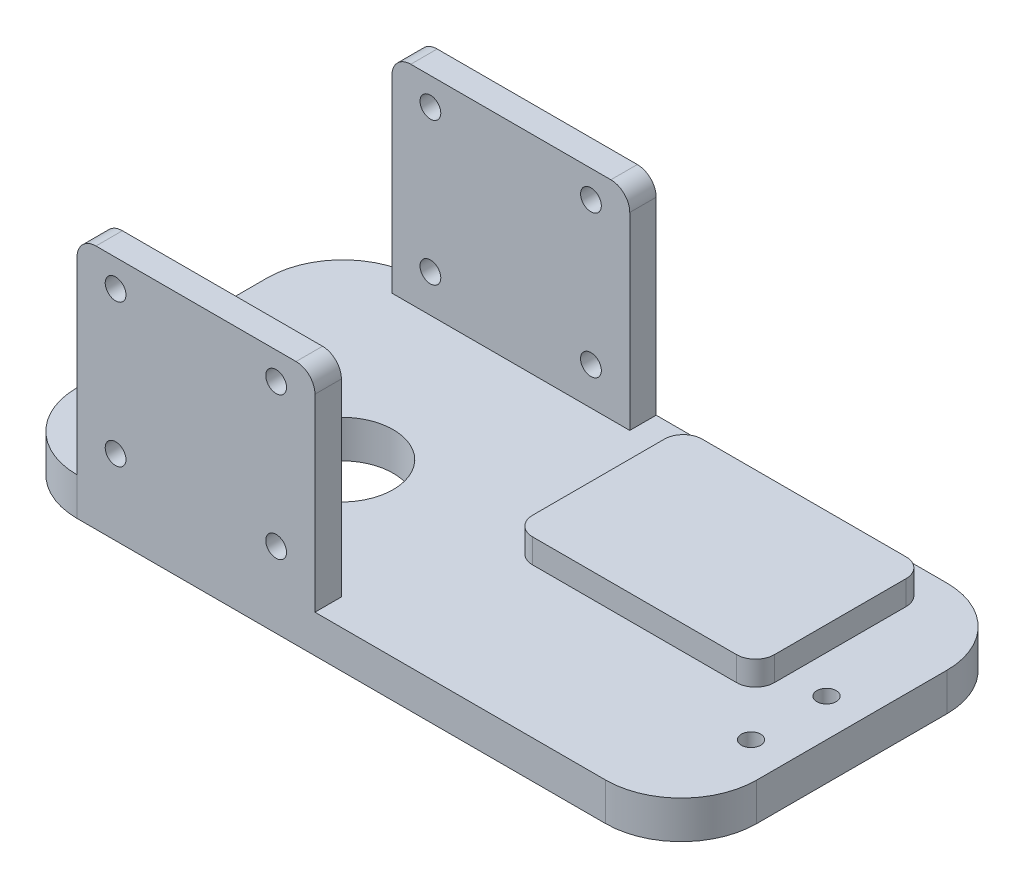
SolidWorks part; units mm, degrees
ref_plane "Front Plane" through (0, 0, 0) normal (0, 0, 1) x (1, 0, 0)
ref_plane "Top Plane" through (0, 0, 0) normal (0, 1, 0) x (1, 0, 0)
ref_plane "Right Plane" through (0, 0, 0) normal (1, 0, 0) x (0, 0, -1)
sketch "Sketch1" plane through (0, 0, 0) normal (0, 1, 0) x (1, 0, 0)
  line L1 (-114.3, -57.39) -> (114.3, -57.39)
  line L2 (-114.3, -57.39) -> (-114.3, 57.39)
  line L3 (-114.3, 57.39) -> (114.3, 57.39)
  line L4 (114.3, -57.39) -> (114.3, 57.39)
  line L5 (-114.3, -57.39) -> (114.3, 57.39) construction
  line L6 (-114.3, 57.39) -> (114.3, -57.39) construction
  point P0 (0, 0)
  dimension "D1" = 114.78
  dimension "D2" = 228.6
extrude "Boss-Extrude1" add sketch "Sketch1" along normal blind 12.7
sketch "Sketch2" plane through (0, 12.7, 0) normal (0, 1, 0) x (1, 0, 0)
  line L1 (-88.9, 57.39) -> (-8.89, 57.39)
  line L2 (-88.9, 57.39) -> (-88.9, 48.5)
  line L3 (-88.9, 48.5) -> (-8.89, 48.5)
  line L4 (-8.89, 57.39) -> (-8.89, 48.5)
  line L5 (-114.3, -57.39) -> (114.3, -57.39) construction
  line L6 (-88.9, -57.39) -> (-8.89, -57.39)
  line L7 (-88.9, -57.39) -> (-88.9, -48.5)
  line L8 (-88.9, -48.5) -> (-8.89, -48.5)
  line L9 (-8.89, -57.39) -> (-8.89, -48.5)
  line L10 (114.3, 57.39) -> (-114.3, 57.39) construction
  line L11 (-114.3, 57.39) -> (-114.3, -57.39) construction
  dimension "D1" = 8.89
  dimension "D2" = 80.01
  dimension "D3" = 25.4
extrude "Boss-Extrude2" add sketch "Sketch2" along normal blind 69.85
sketch "Sketch3" plane through (0, 12.7, 0) normal (0, 1, 0) x (1, 0, 0)
  line L0 (-88.9, 57.39) -> (-88.9, 48.5) construction
  line L1 (88.9, 50) -> (7.62, 50)
  line L2 (88.9, 50) -> (88.9, -7)
  line L3 (88.9, -7) -> (7.62, -7)
  line L4 (7.62, 50) -> (7.62, -7)
  line L5 (114.3, -57.39) -> (114.3, 57.39) construction
  line L8 (114.3, 57.39) -> (-8.89, 57.39) construction
  dimension "D1" = 96.52
  dimension "D2" = 57
  dimension "D3" = 25.4
  dimension "D4" = 7.39
extrude "Boss-Extrude3" add sketch "Sketch3" along normal blind 8.1594
sketch "Sketch4" plane through (0, 12.7, 0) normal (0, 1, 0) x (1, 0, 0)
  line L0 (-88.9, -48.5) -> (-88.9, -57.39) construction
  line L1 (-8.89, -48.5) -> (-88.9, -48.5) construction
  circle A0 centre (-48.9, -8.5) radius 17.4625
  dimension "D3" = 34.925
  dimension "D1" = 40
  dimension "D2" = 40
extrude "Cut-Extrude1" cut sketch "Sketch4" against normal through all
sketch "Sketch5" plane through (0, 0, 57.39) normal (0, 0, 1) x (1, 0, 0)
  line L1 (-88.9, 12.7) -> (-8.89, 12.7) construction
  line L2 (-88.9, 82.55) -> (-88.9, 12.7) construction
  circle A0 centre (-75.946, 73.3594) radius 3.4925
  circle A1 centre (-21.946, 73.3594) radius 3.4925
  circle A2 centre (-75.946, 25.3594) radius 3.4925
  circle A3 centre (-21.946, 25.3594) radius 3.4925
  dimension "D5" = 6.985
  dimension "D1" = 12.6594
  dimension "D2" = 48
  dimension "D3" = 12.954
  dimension "D4" = 54
extrude "Cut-Extrude2" cut sketch "Sketch5" against normal through all
sketch "Sketch6" plane through (0, 12.7, 0) normal (0, 1, 0) x (1, 0, 0)
  line L0 (-114.3, 57.39) -> (-114.3, -57.39) construction
  line L1 (114.3, -57.39) -> (114.3, 57.39) construction
  circle A0 centre (-48.9, -8.5) radius 17.4625 construction
  circle A1 centre (-48.9, -8.5) radius 17.4625
  circle A2 centre (-101.6, -21.2) radius 3.25
  circle A3 centre (-101.6, 4.2) radius 3.25
  circle A4 centre (101.6, -21.2) radius 3.25
  circle A5 centre (101.6, 4.2) radius 3.25
  dimension "D4" = 6.5
  dimension "D5" = 12.7
  dimension "D1" = 12.7
  dimension "D2" = 25.4
  dimension "D3" = 12.7
extrude "Cut-Extrude3" cut sketch "Sketch6" against normal through all
fillet "Fillet1" radius 25.4 4 edges at (114.3, 6.35, -57.39) (114.3, 6.35, 57.39) (-114.3, 6.35, -57.39) (-114.3, 6.35, 57.39)
fillet "Fillet2" radius 6.35 4 edges at (-8.89, 82.55, -52.945) (-88.9, 82.55, -52.945) (-88.9, 82.55, 52.945) (-8.89, 82.55, 52.945)
fillet "Fillet3" radius 6.35 4 edges at (7.62, 16.7797, -50) (7.62, 16.7797, 7) (88.9, 16.7797, 7) (88.9, 16.7797, -50)
